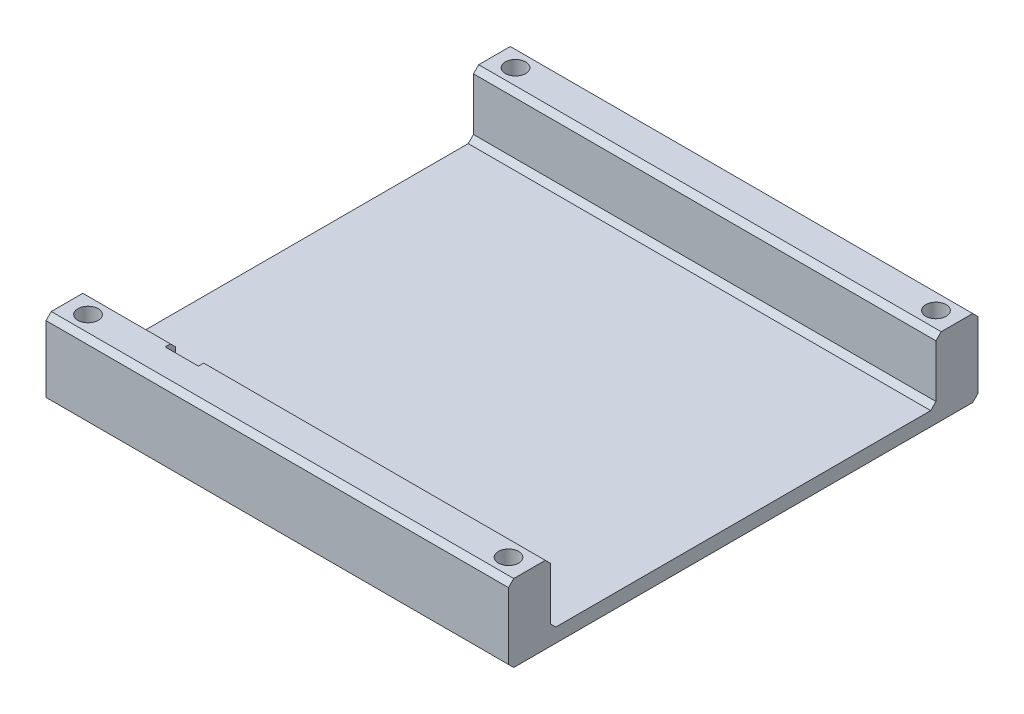
SolidWorks part; units mm, degrees
ref_plane "Front Plane" through (0, 0, 0) normal (0, 0, 1) x (1, 0, 0)
ref_plane "Top Plane" through (0, 0, 0) normal (0, 1, 0) x (1, 0, 0)
ref_plane "Right Plane" through (0, 0, 0) normal (1, 0, 0) x (0, 0, -1)
sketch "Sketch1" plane through (0, 0, 0) normal (0, 1, 0) x (1, 0, 0)
  line L1 (0, 0) -> (66, 0)
  line L2 (0, 0) -> (0, 67)
  line L3 (0, 67) -> (66, 67)
  line L4 (66, 0) -> (66, 67)
  dimension "D1" = 66
  dimension "D2" = 67
extrude "Boss-Extrude1" add sketch "Sketch1" along normal blind 2
sketch "Sketch2" plane through (0, 2, 0) normal (0, 1, 0) x (1, 0, 0)
  line L0 (66, 0) -> (66, 67) construction
  line L1 (0, 67) -> (66, 67)
  line L2 (0, 67) -> (0, 61)
  line L3 (0, 61) -> (66, 61)
  line L4 (66, 67) -> (66, 61)
  line L5 (17.2574, 6) -> (66, 6)
  line L6 (0, 0) -> (66, 0)
  line L7 (0, 0) -> (0, 6)
  line L8 (0, 6) -> (12.5, 6)
  line L9 (66, 0) -> (66, 6)
  line L15 (12.5, 6) -> (12.5, 4.5)
  line L16 (12.5, 4.5) -> (17.2574, 4.5)
  line L17 (17.2574, 6) -> (17.2574, 4.5)
  dimension "D1" = 6
  dimension "D2" = 6
  dimension "D3" = 12.5
  dimension "D4" = 1.5
extrude "Boss-Extrude2" add sketch "Sketch2" along normal blind 9
sketch "Sketch4" plane through (0, 11, 0) normal (0, 1, 0) x (1, 0, 0)
  line L0 (0, 64) -> (66, 64) construction
  line L1 (0, 67) -> (0, 61) construction
  line L2 (66, 61) -> (66, 67) construction
  line L3 (0, 3) -> (66, 3) construction
  line L4 (0, 6) -> (0, 0) construction
  line L5 (66, 0) -> (66, 6) construction
  line L6 (0, 61) -> (0, 6) construction
  circle A0 centre (3, 64) radius 1.45
  circle A1 centre (63, 64) radius 1.45
  circle A2 centre (63, 3) radius 1.45
  circle A3 centre (3, 3) radius 1.45
  dimension "D1" = 2.9
  dimension "D2" = 2.9
  dimension "D3" = 2.9
  dimension "D4" = 2.9
  dimension "D5" = 3
  dimension "D6" = 3
  dimension "D7" = 3
  dimension "D8" = 3
extrude "Cut-Extrude1" cut sketch "Sketch4" against normal blind 3
sketch "Sketch5" plane through (0, 8, 0) normal (0, 1, 0) x (1, 0, 0)
  circle A0 centre (3, 64) radius 1.05
  circle A1 centre (63, 64) radius 1.05
  circle A2 centre (63, 3) radius 1.05
  circle A3 centre (3, 3) radius 1.05
  dimension "D1" = 2.1
  dimension "D2" = 2.1
  dimension "D3" = 2.1
  dimension "D4" = 2.1
extrude "Cut-Extrude2" cut sketch "Sketch5" against normal blind 3
chamfer "Chamfer1" distance 0.75 angle 45 10 edges at (33, 0, -67) (33, 0, 0) (41.6287, 2, -6) (6.25, 2, -6) (6.25, 11, -6) (33, 11, 0) (41.6287, 11, -6) (33, 11, -67) (33, 11, -61) (33, 2, -61)
